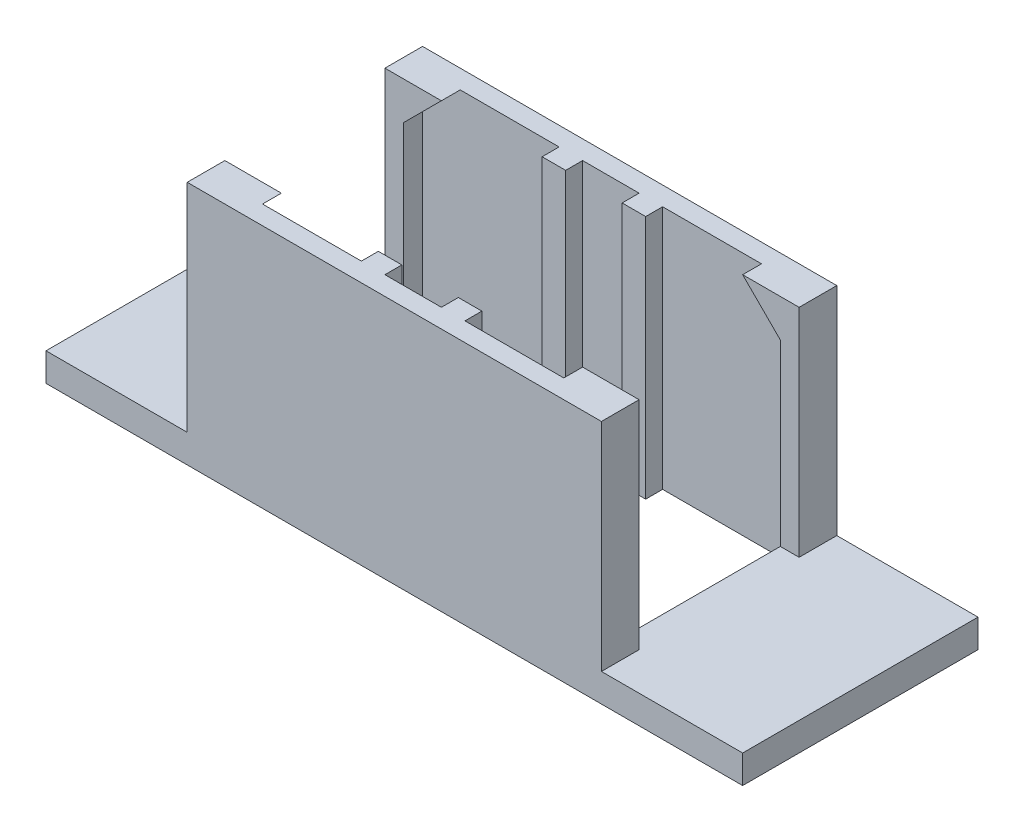
SolidWorks part; units mm, degrees
ref_plane "Płaszczyzna przednia" through (0, 0, 0) normal (0, 0, 1) x (1, 0, 0)
ref_plane "Płaszczyzna górna" through (0, 0, 0) normal (0, 1, 0) x (1, 0, 0)
ref_plane "Płaszczyzna prawa" through (0, 0, 0) normal (1, 0, 0) x (0, 0, -1)
sketch "Sketch1" plane through (0, 0, 0) normal (0, 1, 0) x (1, 0, 0)
  line L0 (-42, 23) -> (2, 23)
  line L1 (-40, 21) -> (0, 21)
  line L2 (-40, 21) -> (-40, 0)
  line L3 (-40, 0) -> (0, 0)
  line L4 (0, 21) -> (0, 0)
  line L5 (2, 23) -> (2, -2)
  line L6 (-42, -2) -> (2, -2)
  line L7 (-42, 23) -> (-42, -2)
  line L8 (-40, 10.5) -> (0, 10.5) construction
  line L9 (-20, 21) -> (-20, 0) construction
  dimension "D1" = 40
  dimension "D2" = 21
  dimension "D3" = 2
extrude "Boss-Extrude1" add sketch "Sketch1" along normal blind 26
sketch "Sketch2" plane through (0, 0, -21) normal (0, 0, 1) x (1, 0, 0)
  line L0 (-40, 0) -> (0, 26) construction
  line L2 (-20, 28.8411) -> (-20, -2.8679) construction
  line L3 (-40, 22) -> (-36, 26)
  line L4 (-36, 26) -> (-40, 26)
  line L5 (-40, 26) -> (-40, 22)
  line L6 (0, 26) -> (0, 22)
  line L7 (-4, 26) -> (0, 26)
  line L8 (0, 22) -> (-4, 26)
  point P3 (-20, 13)
  dimension "D1" = 4
extrude "Boss-Extrude2" add sketch "Sketch2" along normal blind 2
ref_plane "Plane1" through (0, 0, -10.5) normal (0, 0, -1) x (-1, 0, 0)
mirror "Mirror1" about plane through (0, 0, -10.5) normal (0, 0, -1) of "Boss-Extrude2"
sketch "Sketch3" plane through (-40, 0, 0) normal (1, 0, 0) x (0, 0, -1)
  line L1 (2, 26) -> (19, 26)
  line L2 (2, 26) -> (2, 3)
  line L3 (2, 3) -> (19, 3)
  line L4 (19, 26) -> (19, 3)
  line L5 (-2, 0) -> (23, 0) construction
  point P4 (0, 0)
  dimension "D1" = 3
extrude "Cut-Extrude1" cut sketch "Sketch3" against normal mid plane 114
sketch "Sketch4" plane through (0, 0, 0) normal (0, -1, 0) x (1, 0, 0)
  line L0 (-20, 2) -> (-20, -23) construction
  line L1 (-42, -10.5) -> (2, -10.5) construction
  line L2 (-42, 2) -> (2, 2) construction
  line L3 (2, -23) -> (-42, -23) construction
  line L4 (-42, -23) -> (-42, 2) construction
  line L5 (2, 2) -> (2, -23) construction
  line L6 (-40, 0) -> (0, 0) construction
  line L7 (-25.5, 0) -> (-23, 0)
  line L8 (-25.5, 0) -> (-25.5, -1.8)
  line L9 (-25.5, -1.8) -> (-23, -1.8)
  line L10 (-23, 0) -> (-23, -1.8)
  line L11 (-14.5, -1.8) -> (-17, -1.8)
  line L12 (-17, 0) -> (-17, -1.8)
  line L13 (-14.5, 0) -> (-17, 0)
  line L14 (-14.5, 0) -> (-14.5, -1.8)
  line L15 (-14.5, -21) -> (-14.5, -19.2)
  line L16 (-14.5, -21) -> (-17, -21)
  line L17 (-17, -21) -> (-17, -19.2)
  line L18 (-14.5, -19.2) -> (-17, -19.2)
  line L19 (-25.5, -19.2) -> (-23, -19.2)
  line L20 (-23, -21) -> (-23, -19.2)
  line L21 (-25.5, -21) -> (-23, -21)
  line L22 (-25.5, -21) -> (-25.5, -19.2)
  dimension "D1" = 1.8
  dimension "D2" = 2.5
  dimension "D3" = 3
extrude "Boss-Extrude3" add sketch "Sketch4" against normal blind 26
sketch "Sketch8" plane through (2, 0, 0) normal (1, 0, 0) x (0, 0, -1)
  line L1 (-2, 3) -> (23, 3)
  line L2 (-2, 3) -> (-2, 0)
  line L3 (-2, 0) -> (23, 0)
  line L4 (23, 3) -> (23, 0)
  line L5 (19, 3) -> (2, 3) construction
  line L6 (-2, 26) -> (-2, 0) construction
  line L7 (23, 26) -> (23, 0) construction
extrude "Boss-Extrude5" add sketch "Sketch8" along normal blind 15
sketch "Sketch9" plane through (-42, 0, 0) normal (-1, 0, 0) x (0, 0, 1)
  line L0 (-23, 26) -> (-23, 0) construction
  line L1 (-23, 3) -> (2, 3)
  line L2 (-23, 3) -> (-23, 0)
  line L3 (-23, 0) -> (2, 0)
  line L4 (2, 3) -> (2, 0)
  line L5 (2, 26) -> (2, 0) construction
  line L6 (-23, 0) -> (2, 0) construction
  line L7 (-2, 3) -> (-19, 3) construction
  point P12 (-23, 3)
  point P13 (5.2946, 0)
extrude "Boss-Extrude6" add sketch "Sketch9" along normal blind 15
